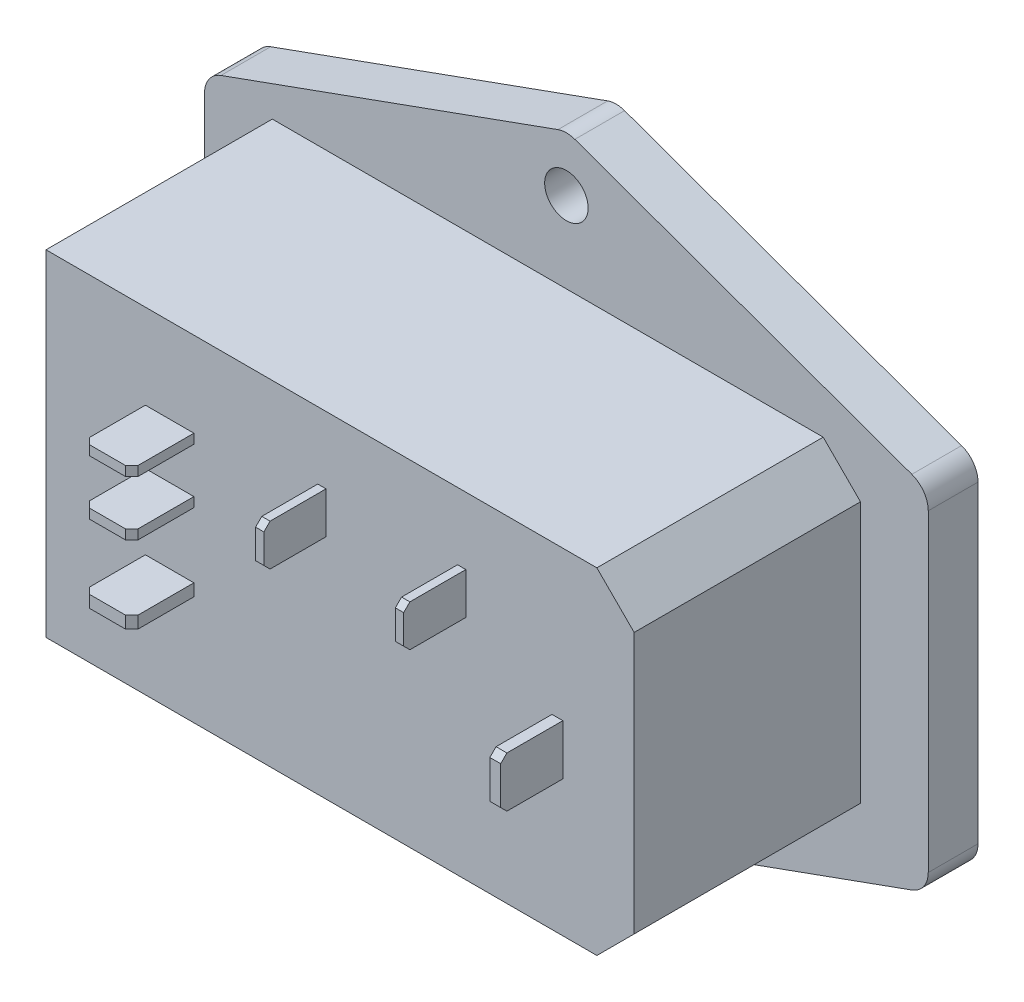
SolidWorks part; units mm, degrees
ref_plane "Alzado" through (0, 0, 0) normal (0, 0, 1) x (1, 0, 0)
ref_plane "Planta" through (0, 0, 0) normal (0, 1, 0) x (1, 0, 0)
ref_plane "Vista lateral" through (0, 0, 0) normal (1, 0, 0) x (0, 0, -1)
sketch "Croquis1" plane through (0, 0, 0) normal (0, 0, 1) x (1, 0, 0)
  line L0 (29.1, -14) -> (29.1, 14)
  line L1 (29.1, 14) -> (0, 24.5)
  line L2 (0, 24.5) -> (-29.1, 14)
  line L3 (-29.1, 14) -> (-29.1, -14)
  line L4 (-29.1, -14) -> (0, -24.5)
  line L5 (0, -24.5) -> (29.1, -14)
extrude "Saliente-Extruir1" add sketch "Croquis1" against normal blind 4
ref_plane "Plano1" through (-16.65, 0, 0) normal (-1, 0, 0) x (0, -1, 0)
sketch "Croquis2" plane through (-16.65, 0, 0) normal (-1, 0, 0) x (0, -1, 0)
  line L0 (-7.9375, -4.6232) -> (9.3124, -9.4464)
  line L1 (9.5663, -9.2538) -> (9.5663, -4)
  line L2 (9.5663, -4) -> (-7.9375, -4)
  line L3 (-7.9375, -4) -> (-7.9375, -4.6232)
  arc A0 (9.3124, -9.4464) -> (9.5663, -9.2538) centre (9.3663, -9.2538) ccw
extrude "Saliente-Extruir2" add sketch "Croquis2" against normal blind 6
sketch "Croquis3" plane through (0, 0, 0) normal (0, 0, 1) x (1, 0, 0)
  line L0 (-23.65, -13.5) -> (-23.65, 13.5)
  line L1 (-23.65, 13.5) -> (23.65, 13.5)
  line L2 (23.65, 13.5) -> (23.65, -13.5)
  line L3 (23.65, -13.5) -> (-23.65, -13.5)
extrude "Saliente-Extruir3" add sketch "Croquis3" along normal blind 18.2
sketch "Croquis4" plane through (0, 0, 18.2) normal (0, 0, 1) x (1, 0, 0)
  line L0 (10.1125, 4.7739) -> (9.4452, 4.7739)
  line L1 (9.4452, 4.7739) -> (9.4452, 8.1106)
  line L2 (9.4452, 8.1106) -> (10.1125, 8.1106)
  line L3 (10.1125, 8.1106) -> (10.1125, 4.7739)
extrude "Saliente-Extruir4" add sketch "Croquis4" along normal blind 5
sketch "Croquis5" plane through (0, 0, 18.2) normal (0, 0, 1) x (1, 0, 0)
  line L0 (-15.6565, -4.7226) -> (-15.6565, -3.7473)
  line L1 (-15.6565, -3.7473) -> (-11.7552, -3.7473)
  line L2 (-11.7552, -3.7473) -> (-11.7552, -4.7226)
  line L3 (-11.7552, -4.7226) -> (-15.6565, -4.7226)
extrude "Saliente-Extruir5" add sketch "Croquis5" along normal blind 5
sketch "Croquis6" plane through (0, 0, 18.2) normal (0, 0, 1) x (1, 0, 0)
  line L0 (-15.6565, 5.9033) -> (-15.6565, 6.6733)
  line L1 (-15.6565, 6.6733) -> (-11.7552, 6.6733)
  line L2 (-11.7552, 6.6733) -> (-11.7552, 5.9033)
  line L3 (-11.7552, 5.9033) -> (-15.6565, 5.9033)
extrude "Saliente-Extruir6" add sketch "Croquis6" along normal blind 5
sketch "Croquis7" plane through (0, 0, 18.2) normal (0, 0, 1) x (1, 0, 0)
  line L0 (-15.6565, 1.4886) -> (-15.6565, 2.2586)
  line L1 (-15.6565, 2.2586) -> (-11.7552, 2.2586)
  line L2 (-11.7552, 2.2586) -> (-11.7552, 1.4886)
  line L3 (-11.7552, 1.4886) -> (-15.6565, 1.4886)
extrude "Saliente-Extruir7" add sketch "Croquis7" along normal blind 5
sketch "Croquis8" plane through (0, 0, 18.2) normal (0, 0, 1) x (1, 0, 0)
  line L0 (-1.1293, 4.7739) -> (-1.7966, 4.7739)
  line L1 (-1.7966, 4.7739) -> (-1.7966, 8.1106)
  line L2 (-1.7966, 8.1106) -> (-1.1293, 8.1106)
  line L3 (-1.1293, 8.1106) -> (-1.1293, 4.7739)
extrude "Saliente-Extruir8" add sketch "Croquis8" along normal blind 5
sketch "Croquis9" plane through (0, 0, 18.2) normal (0, 0, 1) x (1, 0, 0)
  line L0 (17.9151, -2.5666) -> (17.0425, -2.5666)
  line L1 (17.0425, -2.5666) -> (17.0425, 1.4886)
  line L2 (17.0425, 1.4886) -> (17.9151, 1.4886)
  line L3 (17.9151, 1.4886) -> (17.9151, -2.5666)
extrude "Saliente-Extruir9" add sketch "Croquis9" along normal blind 5
sketch "Croquis10" plane through (0, 0, -4) normal (0, 0, -1) x (-1, 0, 0)
  line L0 (-6.8767, 12.15) -> (-23.3767, 12.15)
  line L1 (-23.3767, 12.15) -> (-23.3767, -12.15)
  line L2 (-23.3767, -12.15) -> (-6.8767, -12.15)
  line L3 (-6.8767, -12.15) -> (-6.8767, 12.15)
extrude "Cortar-Extruir1" cut sketch "Croquis10" against normal blind 10
sketch "Croquis11" plane through (0, 0, 6) normal (0, 0, -1) x (-1, 0, 0)
  line L0 (-12.2492, 4.8973) -> (-12.2492, 4.2841)
  line L1 (-12.2492, 4.2841) -> (-15.0791, 4.2841)
  line L2 (-15.0791, 4.2841) -> (-15.0791, 4.8973)
  line L3 (-15.0791, 4.8973) -> (-12.2492, 4.8973)
extrude "Saliente-Extruir10" add sketch "Croquis11" along normal blind 8
sketch "Croquis12" plane through (0, 0, 6) normal (0, 0, -1) x (-1, 0, 0)
  line L0 (-12.2272, -4.6458) -> (-12.2272, -5.3896)
  line L1 (-12.2272, -5.3896) -> (-15.7895, -5.3896)
  line L2 (-15.7895, -5.3896) -> (-15.7895, -4.6458)
  line L3 (-15.7895, -4.6458) -> (-12.2272, -4.6458)
extrude "Saliente-Extruir11" add sketch "Croquis12" along normal blind 8
sketch "Croquis13" plane through (0, 0, 6) normal (0, 0, -1) x (-1, 0, 0)
  line L0 (-17.1205, 0.8347) -> (-17.1205, 0.0127)
  line L1 (-17.1205, 0.0127) -> (-19.8427, 0.0127)
  line L2 (-19.8427, 0.0127) -> (-19.8427, 0.8347)
  line L3 (-19.8427, 0.8347) -> (-17.1205, 0.8347)
extrude "Saliente-Extruir12" add sketch "Croquis13" along normal blind 8
draft "Ángulo de salida1" type of draft neutral plane draft angle 18.435 faces to draft 1 face at (-13.65, 7.9375, -4.3116) neutral plane through (0, 0, -4) neutral plane normal (0, 0, -1) parameters "D1"=18.435
hole_wizard "Diámetro de taladro Ø3.5 (3.5)1" positions "Croquis15" profile "Croquis14" hole size "Ø3.5" standard "Ansi Metric"
sketch "Croquis15" plane through (0, 0, -4) normal (0, 0, -1) x (-1, 0, 0)
  point P0 (0, -20)
  point P1 (0, 20)
sketch "Croquis14" plane through (0, -20, -4) normal (1, 0, 0) x (0, 1, 0)
  line L0 (0, 0) -> (0, 27.2)
  line L1 (0, 27.2) -> (1.75, 27.2)
  line L2 (1.75, 27.2) -> (1.75, 0)
  line L5 (1.75, 0) -> (0, 0)
  line L11 (0, -6.35) -> (0, 107.95) construction
  dimension "Diámetro de taladro hasta el siguiente" = 3.5
  dimension "Profundidad de taladro hasta el siguiente" = 27.2
chamfer "Chaflán1" distance 0.5 angle 45 18 edges at (17.1205, 0.4237, -2) (-11.7552, 6.2883, 23.2) (-15.6565, 1.8736, 23.2) (-1.463, 8.1106, 23.2) (-1.463, 4.7739, 23.2) (-11.7552, 1.8736, 23.2) (17.4788, 1.4886, 23.2) (17.4788, -2.5666, 23.2) (15.0791, 4.5907, -2) (9.7789, 4.7739, 23.2) (-15.6565, -4.2349, 23.2) (-11.7552, -4.2349, 23.2) (-15.6565, 6.2883, 23.2) (12.2272, -5.0177, -2) (19.8427, 0.4237, -2) (12.2492, 4.5907, -2) (9.7789, 8.1106, 23.2) (15.7895, -5.0177, -2)
chamfer "Chaflán2" distance 4.376 angle 37.803 1 edges at (23.3767, -12.15, 1)
chamfer "Chaflán3" distance 1.5 angle 45 2 edges at (-1.75, 20, -4) (-1.75, -20, -4)
chamfer "Chaflán4" distance 3 angle 45 2 edges at (23.65, 13.5, 9.1) (23.65, -13.5, 9.1)
chamfer "Chaflán5" distance 3.3948 angle 52.197 1 edges at (23.3767, 12.15, 1)
fillet "Redondeo1" radius 2 6 edges at (0, -24.5, -2) (29.1, 14, -2) (0, 24.5, -2) (29.1, -14, -2) (-29.1, 14, -2) (-29.1, -14, -2)
